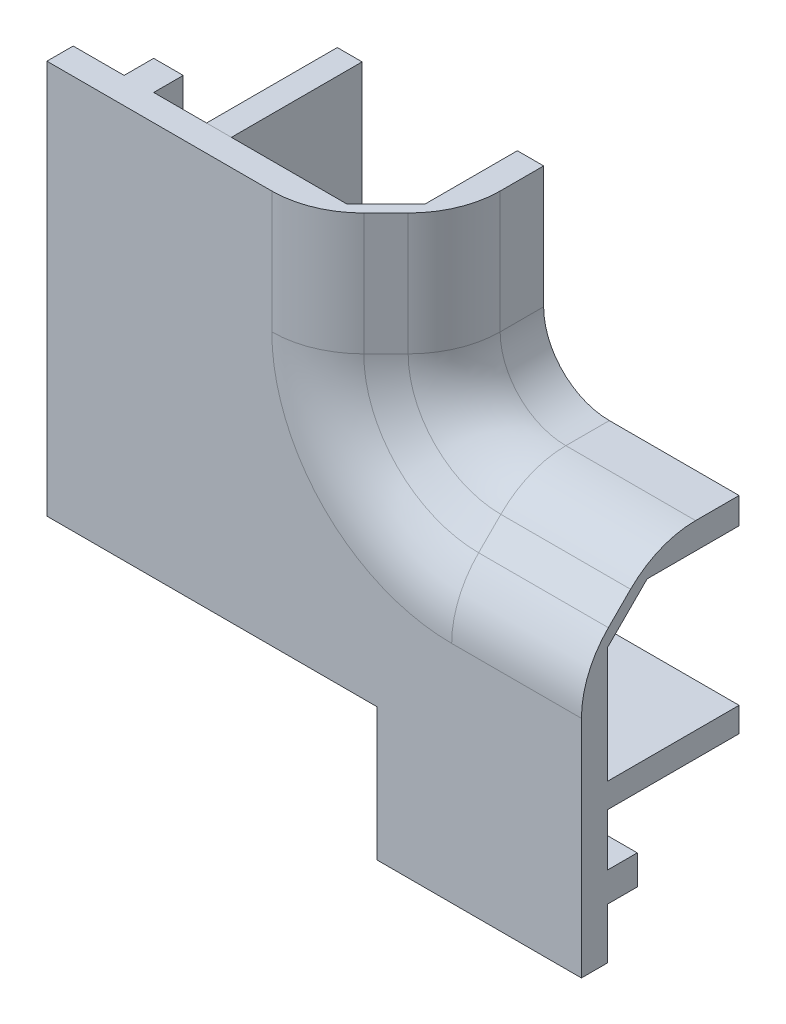
SolidWorks part; units mm, degrees
ref_plane "前基準面" through (0, 0, 0) normal (0, 0, 1) x (1, 0, 0)
ref_plane "上基準面" through (0, 0, 0) normal (0, 1, 0) x (1, 0, 0)
ref_plane "右基準面" through (0, 0, 0) normal (1, 0, 0) x (0, 0, -1)
sketch "草圖1" plane through (0, 0, 0) normal (0, 1, 0) x (1, 0, 0)
  line L0 (-27.5017, 6.8593) -> (-23.0017, 6.8593)
  line L1 (-23.0017, 6.8593) -> (-23.0017, 2.3593)
  line L2 (-23.0017, 2.3593) -> (5.9983, 2.3593)
  line L5 (-27.5017, 6.8593) -> (-27.5017, 2.3593)
  line L6 (-27.5017, 2.3593) -> (-35.2517, 2.3593)
  line L7 (-35.2517, 2.3593) -> (-35.2517, -1.6407)
  line L8 (-35.2517, -1.6407) -> (4.7783, -1.6407)
  line L16 (12.3616, 2.3593) -> (5.9983, 2.3593)
  line L17 (4.7783, -1.6407) -> (16.3616, -1.6407)
  line L19 (12.3616, 2.3593) -> (16.3616, 2.3593)
  line L20 (16.3616, 2.3593) -> (16.3616, -1.6407)
  dimension "D1" = 4.5
  dimension "D2" = 4.5
  dimension "D3" = 4
  dimension "D4" = 4
  dimension "D5" = 7.75
  dimension "D6" = 29
extrude "填料-伸長1" add sketch "草圖1" along normal blind 5
sketch "草圖2" plane through (0, 0, -2.3593) normal (0, 0, -1) x (-1, 0, 0)
  line L0 (-18.0621, -51.2318) -> (-46.1121, -51.2318)
  line L4 (15.0517, 4.8995) -> (15.0517, -25.0006)
  line L5 (-46.1121, -51.2318) -> (-46.1121, -54.9818)
  line L6 (11.2717, -23.1505) -> (11.2717, 4.8995)
  line L7 (15.0517, -25.0006) -> (10.0517, -25.0006)
  line L8 (10.0517, -25.0006) -> (-14.9595, -49.9818)
  line L10 (11.2717, -23.1505) -> (10.0373, -23.1661)
  line L11 (10.0373, -23.1661) -> (-18.0621, -51.2318)
  line L12 (-14.9595, -49.9818) -> (-14.9595, -54.9818)
  line L13 (-14.9595, -54.9818) -> (-24.9595, -54.9818)
  line L16 (11.2717, 4.8995) -> (15.0517, 4.8995)
  line L17 (-46.1121, -54.9818) -> (-24.9595, -54.9818)
  line L18 (23.0017, 5) -> (23.0017, 0) construction
  dimension "D1" = 28.05
  dimension "D2" = 5
  dimension "D3" = 35.35
  dimension "D4" = 5
  dimension "D5" = 10
  dimension "D6" = 28.05
  dimension "D7" = 7.95
  dimension "D8" = 1.3082
  dimension "D9" = 3.75
extrude "填料-伸長2" add sketch "草圖2" along normal blind 20
sketch "草圖4" plane through (0, 0, -2.3593) normal (0, 0, 1) x (1, 0, 0)
  line L1 (46.1121, -54.9818) -> (14.9595, -54.9818) construction
  line L2 (-35.2517, -54.9818) -> (14.9595, -54.9818)
  line L3 (46.1121, -51.2318) -> (46.1121, -54.9818) construction
  line L4 (14.9595, -54.9818) -> (14.9595, -75.1818)
  line L5 (14.9595, -75.1818) -> (46.1121, -75.1818)
  line L6 (14.9595, -54.9818) -> (14.9595, -49.9818) construction
  line L7 (46.1121, -75.1818) -> (46.1121, -23.5718)
  line L11 (46.1121, -23.5718) -> (16.3616, -23.5718)
  line L15 (-35.2517, 0) -> (-35.2517, -54.9818)
  line L17 (-35.2517, 0) -> (16.3616, 0)
  line L18 (16.3616, 0) -> (16.3616, -23.5718)
  point P12 (14.9595, -65.0818)
  dimension "D1" = 51.61
  dimension "D2" = 20.2
  dimension "D3" = 0
  dimension "D4" = 0
extrude "填料-伸長3" add sketch "草圖4" along normal blind 4
sketch "草圖5" plane through (0, 0, -2.3593) normal (0, 0, -1) x (-1, 0, 0)
  line L0 (27.5017, 0) -> (27.5017, -25.0006)
  line L1 (27.5017, -25.0006) -> (23.0017, -25.0006)
  line L2 (23.0017, -25.0006) -> (23.0017, 0)
  line L3 (23.0017, 0) -> (27.5017, 0) construction
  line L4 (23.0017, 0) -> (27.5017, 0) construction
  line L5 (23.0017, 0) -> (27.5017, 0)
  line L6 (-46.1121, -62.9318) -> (-46.1121, -67.4318)
  line L7 (-46.1121, -75.1818) -> (-46.1121, -54.9818) construction
  line L8 (-46.1121, -67.4318) -> (-14.9595, -67.4318)
  line L9 (-14.9595, -54.9818) -> (-14.9595, -75.1818) construction
  line L11 (-14.9595, -75.1818) -> (-46.1121, -75.1818) construction
  line L12 (-46.1121, -62.9318) -> (-14.9595, -62.9318)
  line L13 (-14.9595, -62.9318) -> (-14.9595, -67.4318)
  dimension "D1" = 4.5
  dimension "D2" = 7.75
  dimension "D3" = 4.5
extrude "填料-伸長4" add sketch "草圖5" along normal blind 4.5
sketch "草圖6" plane through (0, 0, -2.3593) normal (0, 0, -1) x (-1, 0, 0)
  line L0 (-16.3616, 5) -> (-16.3616, -23.5718)
  line L1 (-16.3616, -23.5718) -> (-46.1121, -23.5718)
  line L2 (-46.1121, -23.5718) -> (-46.1121, -27.5718)
  line L3 (-46.1121, -51.2318) -> (-46.1121, -23.5718) construction
  line L4 (-46.1121, -27.5718) -> (-12.3616, -27.5718)
  line L5 (-12.3616, -27.5718) -> (-12.3616, 5)
  line L6 (-16.3616, 5) -> (23.0017, 5) construction
  line L7 (-12.3616, 5) -> (-16.3616, 5)
  dimension "D1" = 4
  dimension "D2" = 4
extrude "填料-伸長5" add sketch "草圖6" along normal blind 20
fillet "圓角1" radius 10 1 edges at (16.3616, -23.5718, -10.3593)
fillet "圓角5" radius 6 2 edges at (12.3616, -11.2859, -2.3593) (29.2369, -27.5718, -2.3593) profile chamfer
chamfer "導角7" distance 11.58 angle 45 3 edges at (36.2369, -23.5718, 1.6407) (19.2905, -20.6429, 1.6407) (16.3616, -4.2859, 1.6407)
fillet "圓角6" radius 14 6 edges at (36.2369, -23.5718, -9.9393) (19.2905, -20.6429, -9.9393) (36.2369, -35.1518, 1.6407) (11.1022, -28.8312, 1.6407) (16.3616, -4.2859, -9.9393) (4.7816, -4.2859, 1.6407)
ref_plane "平面2" through (0, 7, 0) normal (0, 1, 0) x (1, 0, 0)
